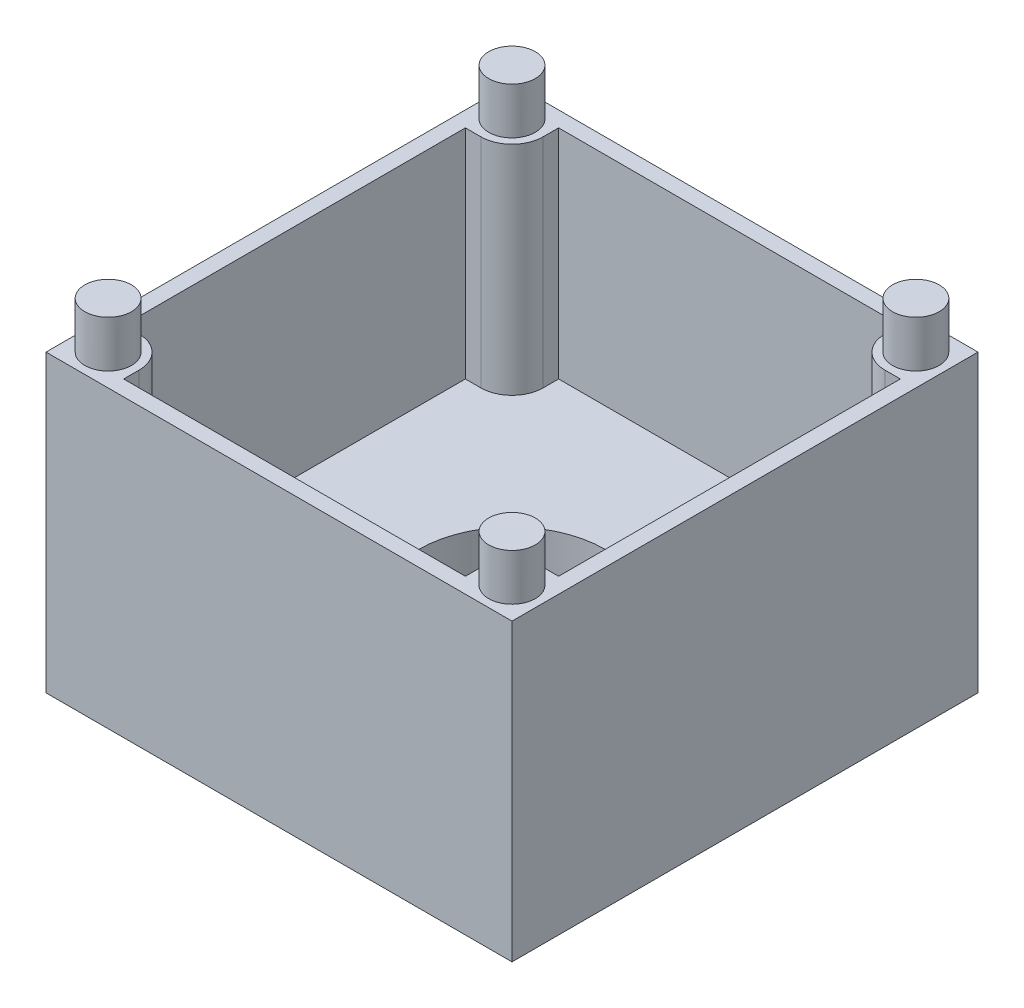
SolidWorks part; units mm, degrees
ref_plane "前视基准面" through (0, 0, 0) normal (0, 0, 1) x (1, 0, 0)
ref_plane "上视基准面" through (0, 0, 0) normal (0, 1, 0) x (1, 0, 0)
ref_plane "右视基准面" through (0, 0, 0) normal (1, 0, 0) x (0, 0, -1)
sketch "草图1" plane through (0, 0, 0) normal (0, 1, 0) x (1, 0, 0)
  line L1 (-7.5, -7.5) -> (7.5, -7.5)
  line L2 (-7.5, -7.5) -> (-7.5, 7.5)
  line L3 (-7.5, 7.5) -> (7.5, 7.5)
  line L4 (7.5, -7.5) -> (7.5, 7.5)
extrude "凸台-拉伸1" add sketch "草图1" along normal blind 9.5
sketch "草图2" plane through (0, 9.5, 0) normal (0, 1, 0) x (-1, 0, 0)
  line L0 (6.5, -5.5) -> (7, -5.5)
  line L1 (5.5, 7) -> (-5.5, 7)
  line L2 (7, 5.5) -> (7, -5.5)
  line L3 (5.5, -7) -> (-5.5, -7)
  line L4 (-7, 5.5) -> (-7, -5.5)
  line L5 (5.5, -6.5) -> (5.5, -7)
  line L6 (-6.5, -5.5) -> (-7, -5.5)
  line L7 (-5.5, -6.5) -> (-5.5, -7)
  line L8 (6.5, 5.5) -> (7, 5.5)
  line L9 (5.5, 6.5) -> (5.5, 7)
  line L10 (-5.5, 6.5) -> (-5.5, 7)
  line L11 (-6.5, 5.5) -> (-7, 5.5)
  arc A0 (6.5, -5.5) -> (5.5, -6.5) centre (6.5, -6.5) ccw
  arc A1 (-6.5, 5.5) -> (-5.5, 6.5) centre (-6.5, 6.5) ccw
  arc A2 (5.5, 6.5) -> (6.5, 5.5) centre (6.5, 6.5) ccw
  arc A3 (-5.5, -6.5) -> (-6.5, -5.5) centre (-6.5, -6.5) ccw
extrude "切除-拉伸1" cut sketch "草图2" against normal blind 7
sketch "草图5" plane through (0, 9.5, 0) normal (0, 1, 0) x (-1, 0, 0)
  circle A0 centre (6.5, -6.5) radius 0.75
  circle A1 centre (6.5, 6.5) radius 0.75
  circle A2 centre (-6.5, 6.5) radius 0.75
  circle A3 centre (-6.5, -6.5) radius 0.75
extrude "凸台-拉伸2" add sketch "草图5" along normal blind 1.5
sketch "草图6" plane through (0, 0, 0) normal (0, -1, 0) x (1, 0, 0)
  circle A0 centre (0, 0) radius 3
extrude "切除-拉伸2" cut sketch "草图6" against normal up to next
